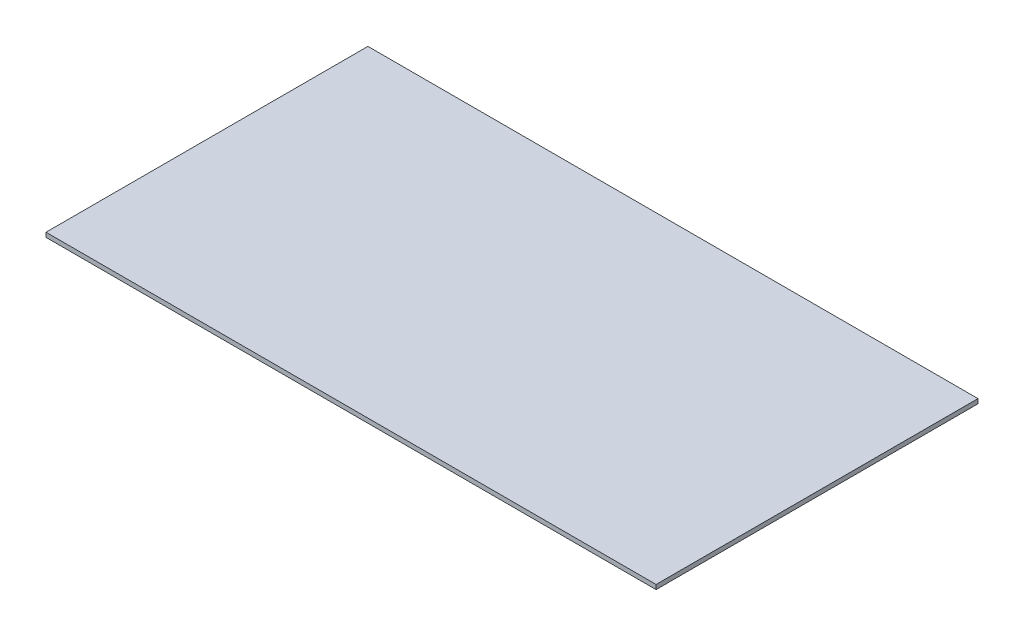
SolidWorks part; units mm, degrees
ref_plane "Front Plane" through (0, 0, 0) normal (0, 0, 1) x (1, 0, 0)
ref_plane "Top Plane" through (0, 0, 0) normal (0, 1, 0) x (1, 0, 0)
ref_plane "Right Plane" through (0, 0, 0) normal (1, 0, 0) x (0, 0, -1)
sketch "Sketch1" plane through (0, 0, 0) normal (0, 1, 0) x (1, 0, 0)
  line L1 (0, 0) -> (431.8, 0)
  line L2 (0, 0) -> (0, 227.838)
  line L3 (0, 227.838) -> (431.8, 227.838)
  line L4 (431.8, 0) -> (431.8, 227.838)
  dimension "D1" = 431.8
  dimension "D2" = 227.838
extrude "Boss-Extrude1" add sketch "Sketch1" along normal blind 3.175
